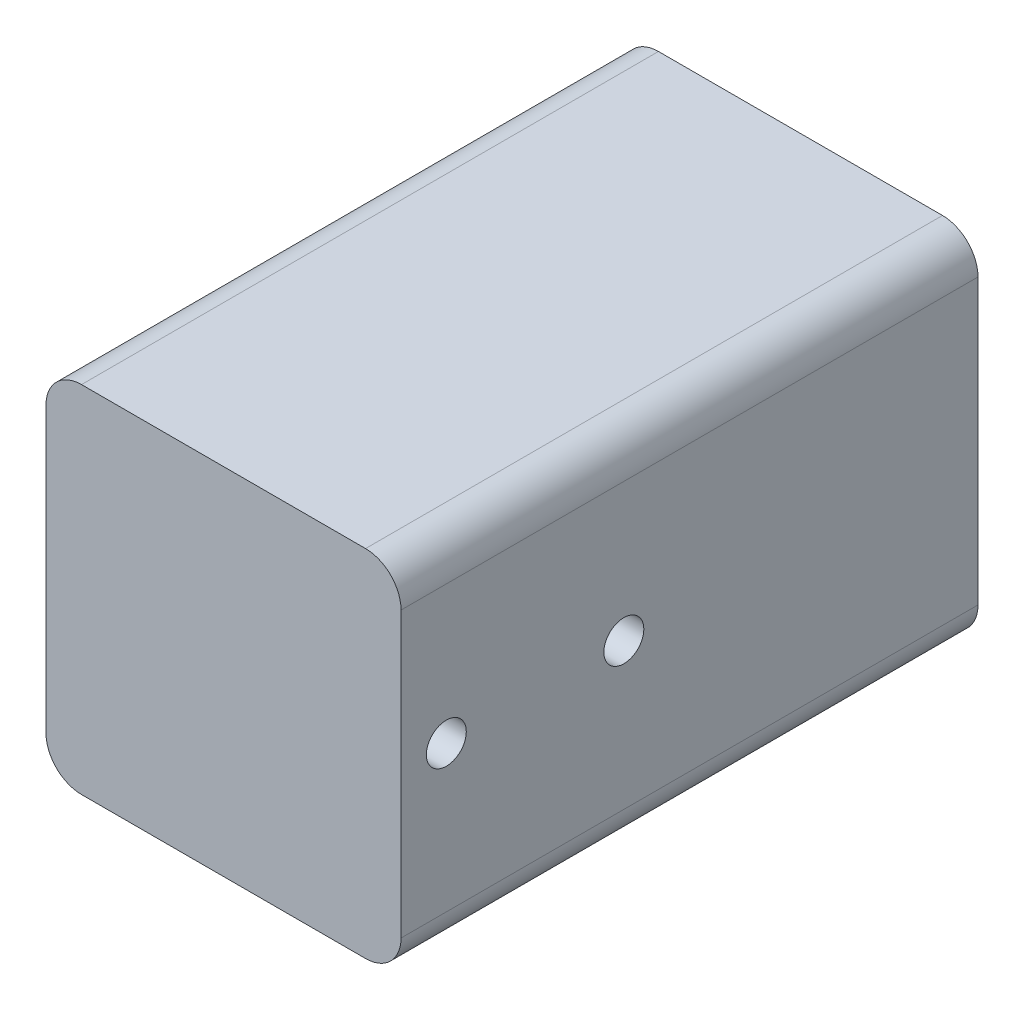
SolidWorks part; units mm, degrees
ref_plane "Front Plane" through (0, 0, 0) normal (0, 0, 1) x (1, 0, 0)
ref_plane "Top Plane" through (0, 0, 0) normal (0, 1, 0) x (1, 0, 0)
ref_plane "Right Plane" through (0, 0, 0) normal (1, 0, 0) x (0, 0, -1)
sketch "Sketch1" plane through (0, 0, 0) normal (0, 0, 1) x (1, 0, 0)
  line L1 (-16, -20) -> (16, -20)
  line L2 (-20, -16) -> (-20, 16)
  line L3 (-16, 20) -> (16, 20)
  line L4 (20, -16) -> (20, 16)
  line L5 (-20, -20) -> (20, 20) construction
  line L6 (-20, 20) -> (20, -20) construction
  arc A0 (-20, -16) -> (-16, -20) centre (-16, -16) ccw
  arc A1 (16, -20) -> (20, -16) centre (16, -16) ccw
  arc A2 (20, 16) -> (16, 20) centre (16, 16) ccw
  arc A3 (-20, 16) -> (-16, 20) centre (-16, 16) cw
  point P0 (0, 0)
  dimension "D3" = 4
  dimension "D1" = 40
  dimension "D2" = 40
extrude "Boss-Extrude1" add sketch "Sketch1" along normal blind 65
sketch "Sketch2" plane through (0, 0, 0) normal (0, 0, -1) x (-1, 0, 0)
  line L0 (18.8284, 18.8284) -> (-18.8284, -18.8284) construction
  line L1 (-18.8284, 18.8284) -> (18.8284, -18.8284) construction
  arc A0 (20, 16) -> (16, 20) centre (16, 16) ccw construction
  arc A1 (-20, -16) -> (-16, -20) centre (-16, -16) ccw construction
  arc A2 (-16, 20) -> (-20, 16) centre (-16, 16) ccw construction
  arc A3 (16, -20) -> (20, -16) centre (16, -16) ccw construction
  circle A4 centre (0, 0) radius 17.5 construction
  circle A5 centre (-12.3744, 12.3744) radius 0.5124
  circle A6 centre (12.3744, 12.3744) radius 0.5124
  circle A7 centre (12.3744, -12.3744) radius 0.5124
  circle A8 centre (-12.3744, -12.3744) radius 0.5124
  point P29 (0, 0)
  dimension "D1" = 35
  dimension "D2" = 4
extrude "Cut-Extrude1" cut sketch "Sketch2" against normal blind 3
hole_wizard "M6 Clearance Hole1" positions "Sketch4" profile "Sketch3" hole size "M6" standard "ANSI Metric"
sketch "Sketch4" plane through (0, 0, 0) normal (0, 0, -1) x (-1, 0, 0)
  point P0 (12.3744, 12.3744)
  point P3 (-12.3744, 12.3744)
  point P6 (-12.3744, -12.3744)
  point P9 (12.3744, -12.3744)
sketch "Sketch3" plane through (-12.3744, 12.3744, 0) normal (1, 0, 0) x (0, 1, 0)
  line L0 (0, 0) -> (0, 6.9828)
  line L1 (0, 6.9828) -> (3.3, 5)
  line L2 (3.3, 5) -> (3.3, 0)
  line L5 (3.3, 0) -> (0, 0)
  line L10 (0, 6.9828) -> (-3.3, 5) construction
  line L11 (0, -6.35) -> (0, 107.95) construction
  dimension "Hole Dia." = 6.6
  dimension "Hole Depth" = 5
  dimension "Drill Angle" = 118
hole_wizard "M4 Clearance Hole1" positions "Sketch7" profile "Sketch5" hole size "M4" standard "ANSI Metric"
sketch "Sketch7" plane through (20, 0, 0) normal (1, 0, 0) x (0, 0, -1)
  point P0 (-59.9, 0.4605)
  point P3 (-39.9, 0.4605)
sketch "Sketch5" plane through (20, 0.4605, 59.9) normal (0, 1, 0) x (0, 0, -1)
  line L0 (0, 0) -> (0, 6.3519)
  line L1 (0, 6.3519) -> (2.25, 5)
  line L2 (2.25, 5) -> (2.25, 0)
  line L5 (2.25, 0) -> (0, 0)
  line L10 (0, 6.3519) -> (-2.25, 5) construction
  line L11 (0, -6.35) -> (0, 107.95) construction
  dimension "Hole Dia." = 4.5
  dimension "Hole Depth" = 5
  dimension "Drill Angle" = 118
